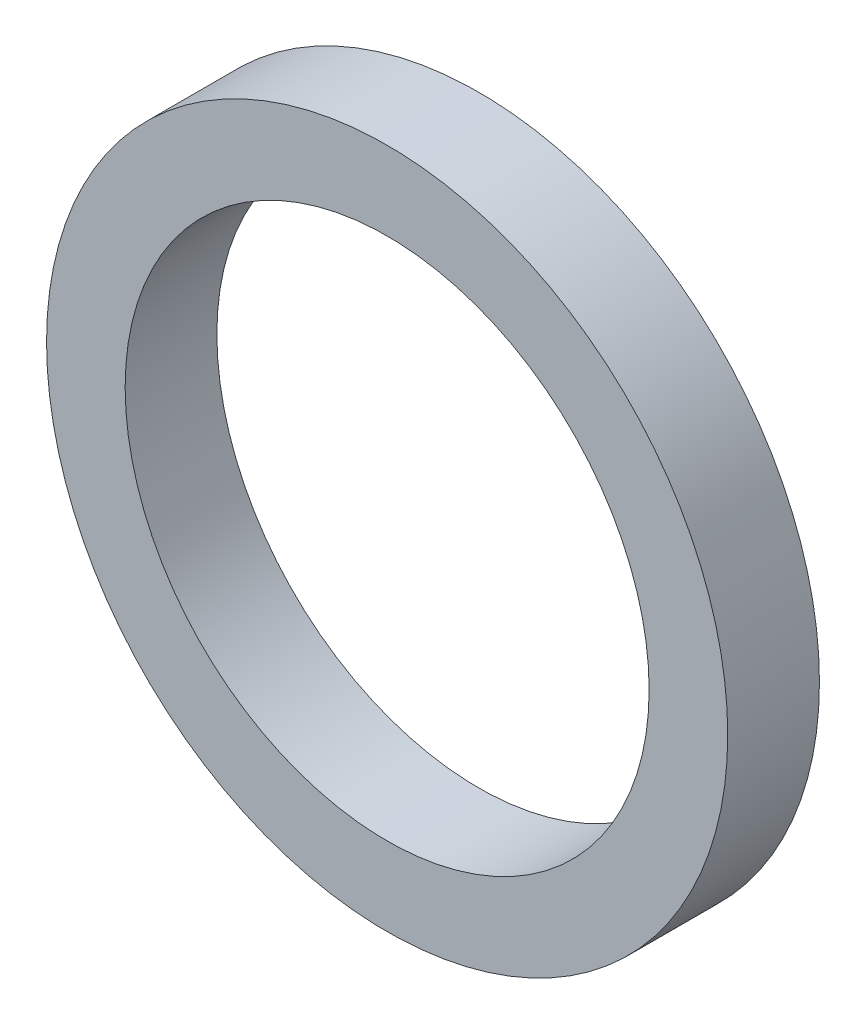
SolidWorks part; units mm, degrees
ref_plane "Front Plane" through (0, 0, 0) normal (0, 0, 1) x (1, 0, 0)
ref_plane "Top Plane" through (0, 0, 0) normal (0, 1, 0) x (1, 0, 0)
ref_plane "Right Plane" through (0, 0, 0) normal (1, 0, 0) x (0, 0, -1)
sketch "S01 - Annular section" plane through (0, 0, 0) normal (0, 0, 1) x (1, 0, 0)
  circle A0 centre (0, 0) radius 26
  circle A1 centre (0, 0) radius 20
  dimension "D1" = 40
  dimension "D2" = 52
extrude "01 - Annular section" add sketch "S01 - Annular section" along normal blind 7
